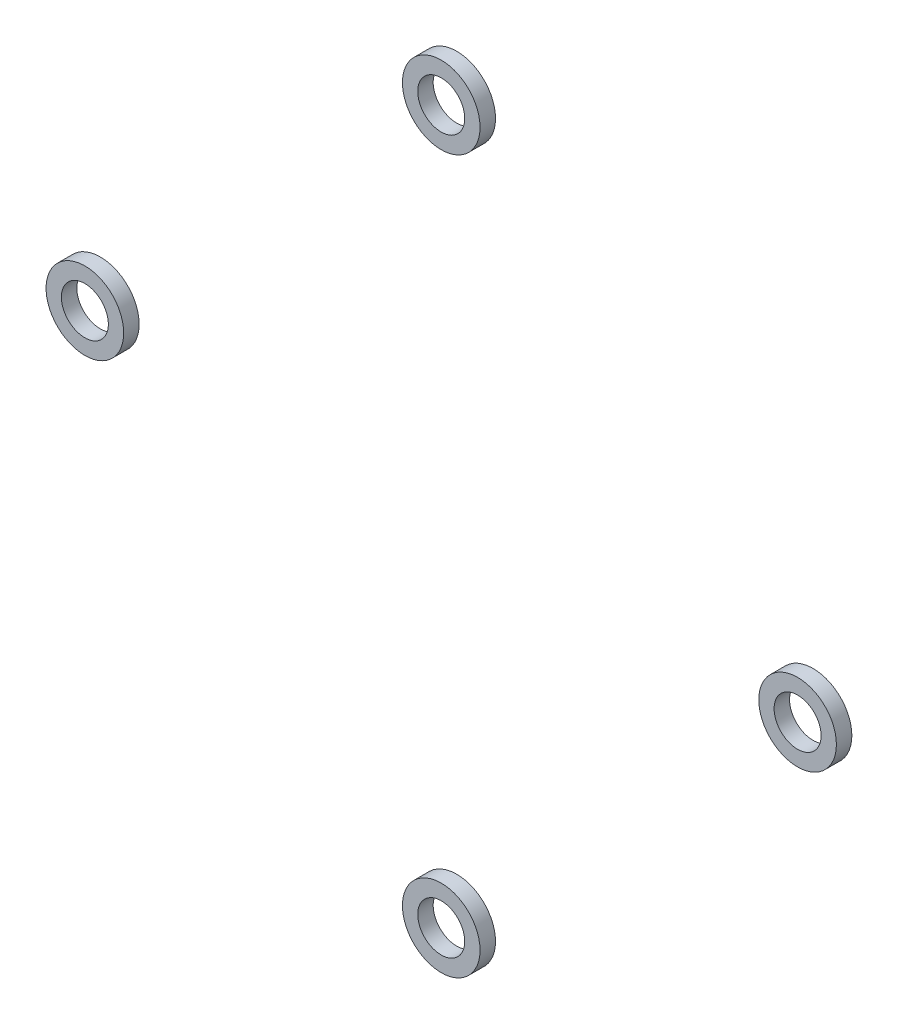
SolidWorks part; units mm, degrees
material "黄铜"
ref_plane "前视基准面" through (0, 0, 0) normal (0, 0, 1) x (1, 0, 0)
ref_plane "上视基准面" through (0, 0, 0) normal (0, 1, 0) x (1, 0, 0)
ref_plane "右视基准面" through (0, 0, 0) normal (1, 0, 0) x (0, 0, -1)
ref_plane "基准面1" through (0, 0, 53) normal (0, 0, 1) x (1, 0, 0)
sketch "草图1" plane through (0, 0, 53) normal (0, 0, 1) x (1, 0, 0)
  circle A0 centre (-24.6985, 21.5378) radius 1.52
  circle A1 centre (-24.6985, 21.5378) radius 2.51
  circle A2 centre (-1.6485, -1.5122) radius 1.52
  circle A3 centre (-1.6485, -1.5122) radius 2.51
  circle A4 centre (-24.6985, -24.5622) radius 1.52
  circle A5 centre (-24.6985, -24.5622) radius 2.51
  circle A6 centre (-47.7485, -1.5122) radius 1.52
  circle A7 centre (-47.7485, -1.5122) radius 2.51
  point P16 (-24.6985, -1.5122)
  dimension "D1" = 4
extrude "凸台-拉伸1" add sketch "草图1" along normal blind 1
